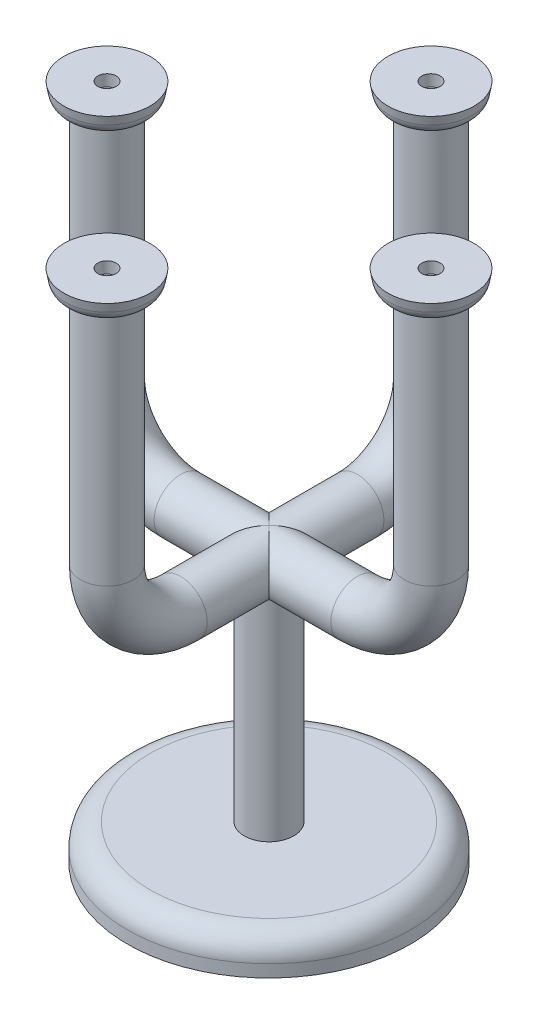
SolidWorks part; units mm, degrees
ref_plane "Front Plane" through (0, 0, 0) normal (0, 0, 1) x (1, 0, 0)
ref_plane "Top Plane" through (0, 0, 0) normal (0, 1, 0) x (1, 0, 0)
ref_plane "Right Plane" through (0, 0, 0) normal (1, 0, 0) x (0, 0, -1)
sketch "Sketch1" plane through (0, 0, 0) normal (0, 0, 1) x (1, 0, 0)
  line L0 (0, 0) -> (0, 150)
  line L1 (0, 150) -> (14, 150)
  line L2 (14, 150) -> (14, 20)
  line L3 (14, 20) -> (67, 20)
  line L4 (80, 7) -> (80, 0)
  line L5 (80, 0) -> (0, 0)
  arc A0 (67, 20) -> (80, 7) centre (67, 7) cw
  point P9 (80, 20)
  dimension "D5" = 13
  dimension "D1" = 150
  dimension "D2" = 20
  dimension "D3" = 80
  dimension "D4" = 14
revolve "Revolve1" add sketch "Sketch1" angle 360 about L0
sketch "Sketch2" plane through (0, 0, 0) normal (0, 0, 1) x (1, 0, 0)
  line L1 (0, 150) -> (49.9286, 150)
  line L2 (14, 150) -> (-14, 150) construction
  line L3 (91.568, 191.6394) -> (91.568, 325.398)
  arc A0 (49.9286, 150) -> (91.568, 191.6394) centre (49.9286, 191.6394) ccw
sweep "Sweep1" add path "Sketch2" circular profile diameter 30 parameters "D3"=30
pattern_circular "CirPattern1" count 4 over 360 about axis through (0, 0, 0) along (0, 1, 0) of "Sweep1"
sketch "Sketch17" plane through (0, 325.398, 0) normal (0, 1, 0) x (1, 0, 0)
  point P0 (0, -91.568)
  point P1 (-74.5835, 37.6253)
ref_plane "Plane2" through (0, 0, 91.568) normal (0, 0, 1) x (1, 0, 0)
sketch "Sketch18" plane through (0, 0, 91.568) normal (0, 0, 1) x (1, 0, 0)
  line L0 (0, 325.398) -> (15.943, 325.398)
  line L1 (23.466, 331.6765) -> (24.3594, 336.5903)
  line L2 (24.3594, 336.5903) -> (5.1721, 336.5903)
  line L4 (0, 330.1107) -> (0, 325.398)
  line L8 (0, 330.1107) -> (5.1721, 330.1107)
  line L9 (5.1721, 336.5903) -> (5.1721, 330.1107)
  arc A0 (15.943, 325.398) -> (23.466, 331.6765) centre (15.943, 333.0443) ccw
  dimension "D4" = 7.6463
  dimension "D1" = 19.1873
  dimension "D2" = 6.4796
  dimension "D3" = 5.1721
  dimension "D5" = 4.9138
revolve "Revolve2" add sketch "Sketch18" angle 360 about L4
pattern_circular "CirPattern2" count 4 over 360 about axis through (0, 0, 0) along (0, 1, 0) of "Revolve2"
